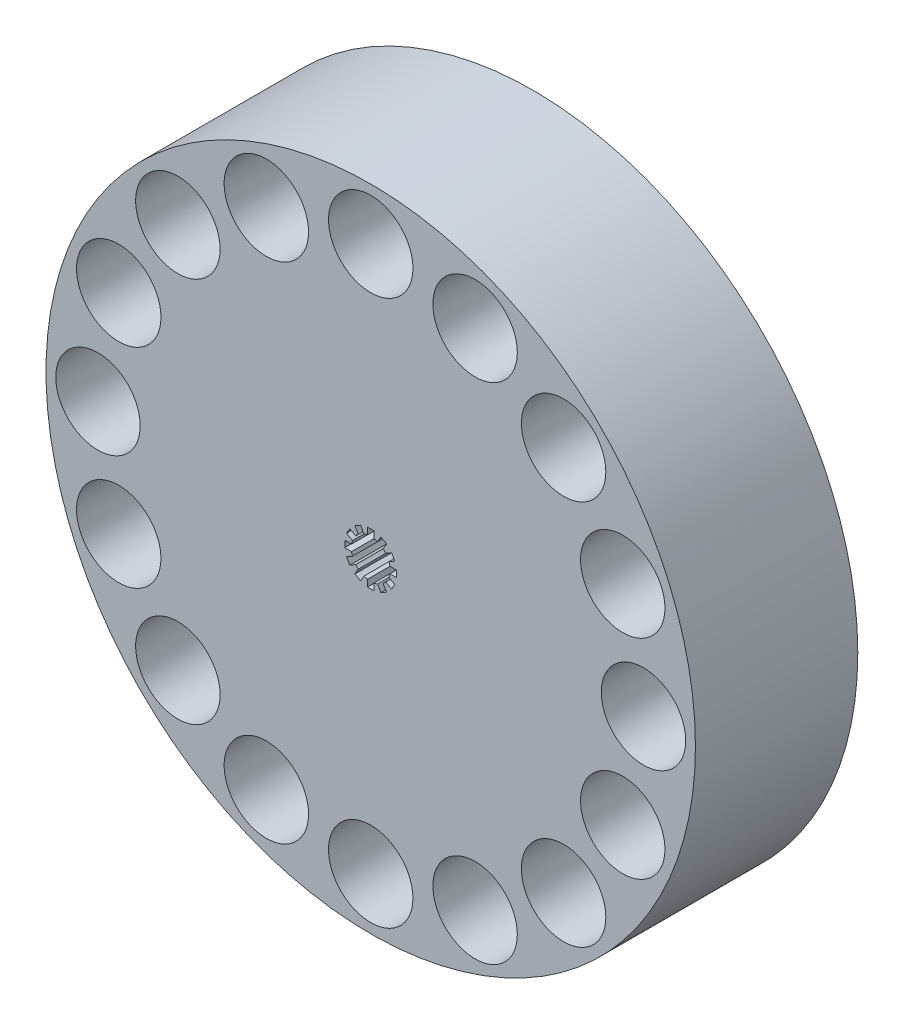
SolidWorks part; units mm, degrees
ref_plane "Front Plane" through (0, 0, 0) normal (1, 0, 0) x (0, 1, 0)
ref_plane "Top Plane" through (0, 0, 0) normal (0, 0, 1) x (0, 1, 0)
ref_plane "Right Plane" through (0, 0, 0) normal (0, 1, 0) x (-1, 0, 0)
sketch "Sketch2" plane through (0, 0, 0) normal (0, 0, 1) x (0, 1, 0)
  line L0 (0, -42) -> (0, 42) construction
  line L1 (-42, 0) -> (42, 0) construction
  line L2 (29.6985, -29.6985) -> (-29.6985, 29.6985) construction
  line L3 (-29.6985, -29.6985) -> (29.6985, 29.6985) construction
  line L4 (38.8029, -16.0727) -> (-38.8029, 16.0727) construction
  line L5 (16.0727, -38.8029) -> (-16.0727, 38.8029) construction
  line L6 (-16.0727, -38.8029) -> (16.0727, 38.8029) construction
  line L7 (-38.8029, -16.0727) -> (38.8029, 16.0727) construction
  circle A1 centre (0, 0) radius 50
  circle A2 centre (0, 42) radius 6.5
  circle A3 centre (29.6985, 29.6985) radius 6.5
  circle A4 centre (42, 0) radius 6.5
  circle A5 centre (29.6985, -29.6985) radius 6.5
  circle A6 centre (0, -42) radius 6.5
  circle A7 centre (-29.6985, -29.6985) radius 6.5
  circle A8 centre (-42, 0) radius 6.5
  circle A9 centre (-29.6985, 29.6985) radius 6.5
  circle A10 centre (-38.8029, 16.0727) radius 6.5
  circle A11 centre (-16.0727, 38.8029) radius 6.5
  circle A12 centre (16.0727, 38.8029) radius 6.5
  circle A13 centre (38.8029, 16.0727) radius 6.5
  circle A14 centre (38.8029, -16.0727) radius 6.5
  circle A15 centre (16.0727, -38.8029) radius 6.5
  circle A16 centre (-16.0727, -38.8029) radius 6.5
  circle A17 centre (-38.8029, -16.0727) radius 6.5
  point P7 (0, 0)
  point P10 (0, 0)
  point P13 (0, 0)
  point P16 (0, 0)
  point P26 (0, 0)
  point P30 (0, 0)
  point P33 (0, 0)
  point P36 (0, 0)
  dimension "D2" = 100
  dimension "D9" = 13
  dimension "D10" = 13
  dimension "D11" = 13
  dimension "11" = 13
  dimension "D13" = 13
  dimension "D14" = 13
  dimension "D15" = 13
  dimension "D16" = 13
  dimension "D25" = 13
  dimension "D26" = 13
  dimension "D27" = 13
  dimension "D28" = 13
  dimension "D29" = 13
  dimension "D30" = 13
  dimension "D31" = 13
  dimension "D32" = 13
  dimension "D3" = 84
  dimension "D4" = 84
  dimension "D5" = 84
  dimension "D6" = 84
  dimension "D7" = 45
  dimension "D8" = 45
  dimension "D17" = 84
  dimension "D18" = 84
  dimension "D19" = 84
  dimension "D20" = 84
  dimension "D21" = 22.5
  dimension "D22" = 22.5
  dimension "D23" = 22.5
  dimension "D24" = 22.5
extrude "Boss-Extrude1" add sketch "Sketch2" along normal blind 25
sketch "Sketch4" plane through (0, 0, 25) normal (0, 0, 1) x (1, 0, 0)
  line L1 (-0.5, 4) -> (0.5, 4)
  line L2 (-0.5, 4) -> (-0.5, 2.958)
  line L3 (-0.5, -4) -> (0.5, -4)
  line L4 (0.5, 4) -> (0.5, 2.958)
  line L7 (-4, 0.5) -> (-2.958, 0.5)
  line L8 (-4, 0.5) -> (-4, -0.5)
  line L9 (-4, -0.5) -> (-2.958, -0.5)
  line L10 (4, 0.5) -> (4, -0.5)
  line L15 (1.567, -3.7141) -> (1.046, -2.8117)
  line L16 (-1.567, 3.7141) -> (-2.433, 3.2141)
  line L17 (2.433, -3.2141) -> (1.912, -2.3117)
  line L18 (2.433, -3.2141) -> (1.567, -3.7141)
  line L19 (-3.2141, -2.433) -> (-3.7141, -1.567)
  line L20 (3.2141, 2.433) -> (2.3117, 1.912)
  line L21 (3.7141, 1.567) -> (3.2141, 2.433)
  line L22 (3.7141, 1.567) -> (2.8117, 1.046)
  line L23 (2.433, 3.2141) -> (1.567, 3.7141)
  line L24 (-2.433, -3.2141) -> (-1.912, -2.3117)
  line L25 (-1.567, -3.7141) -> (-2.433, -3.2141)
  line L26 (-1.567, -3.7141) -> (-1.046, -2.8117)
  line L27 (-3.7141, 1.567) -> (-3.2141, 2.433)
  line L28 (3.7141, -1.567) -> (2.8117, -1.046)
  line L29 (3.2141, -2.433) -> (3.7141, -1.567)
  line L30 (3.2141, -2.433) -> (2.3117, -1.912)
  line L31 (-1.046, 2.8117) -> (-1.567, 3.7141)
  line L34 (0, 4) -> (0, 5.58) construction
  line L37 (1.046, 2.8117) -> (1.567, 3.7141)
  line L38 (2, 3.4641) -> (3.1042, 5.3767) construction
  line L39 (1.912, 2.3117) -> (2.433, 3.2141)
  line L41 (3.4641, 2) -> (6.1174, 3.5319) construction
  line L43 (2.958, 0.5) -> (4, 0.5)
  line L46 (2.958, -0.5) -> (4, -0.5)
  line L51 (0.5, -2.958) -> (0.5, -4)
  line L54 (-0.5, -2.958) -> (-0.5, -4)
  line L57 (-2.3117, -1.912) -> (-3.2141, -2.433)
  line L58 (-2.8117, -1.046) -> (-3.7141, -1.567)
  line L63 (-2.8117, 1.046) -> (-3.7141, 1.567)
  line L64 (-2.3117, 1.912) -> (-3.2141, 2.433)
  line L65 (-1.912, 2.3117) -> (-2.433, 3.2141)
  arc A0 (-1.912, 2.3117) -> (-2.3117, 1.912) centre (0, 0) ccw
  arc A1 (-0.5, 2.958) -> (-1.046, 2.8117) centre (0, 0) ccw
  arc A2 (1.046, 2.8117) -> (0.5, 2.958) centre (0, 0) ccw
  arc A3 (2.3117, 1.912) -> (1.912, 2.3117) centre (0, 0) ccw
  arc A4 (2.958, 0.5) -> (2.8117, 1.046) centre (0, 0) ccw
  arc A5 (2.8117, -1.046) -> (2.958, -0.5) centre (0, 0) ccw
  arc A6 (1.912, -2.3117) -> (2.3117, -1.912) centre (0, 0) ccw
  arc A7 (0.5, -2.958) -> (1.046, -2.8117) centre (0, 0) ccw
  arc A8 (-1.046, -2.8117) -> (-0.5, -2.958) centre (0, 0) ccw
  arc A9 (-2.3117, -1.912) -> (-1.912, -2.3117) centre (0, 0) ccw
  arc A10 (-2.958, -0.5) -> (-2.8117, -1.046) centre (0, 0) ccw
  arc A11 (-2.8117, 1.046) -> (-2.958, 0.5) centre (0, 0) ccw
  dimension "D1" = 6
  dimension "D2" = 1
  dimension "D3" = 8
  dimension "D4" = 1
  dimension "D5" = 8
  dimension "D6" = 30
  dimension "D7" = 60
extrude "Cut-Extrude1" cut sketch "Sketch4" against normal through all
